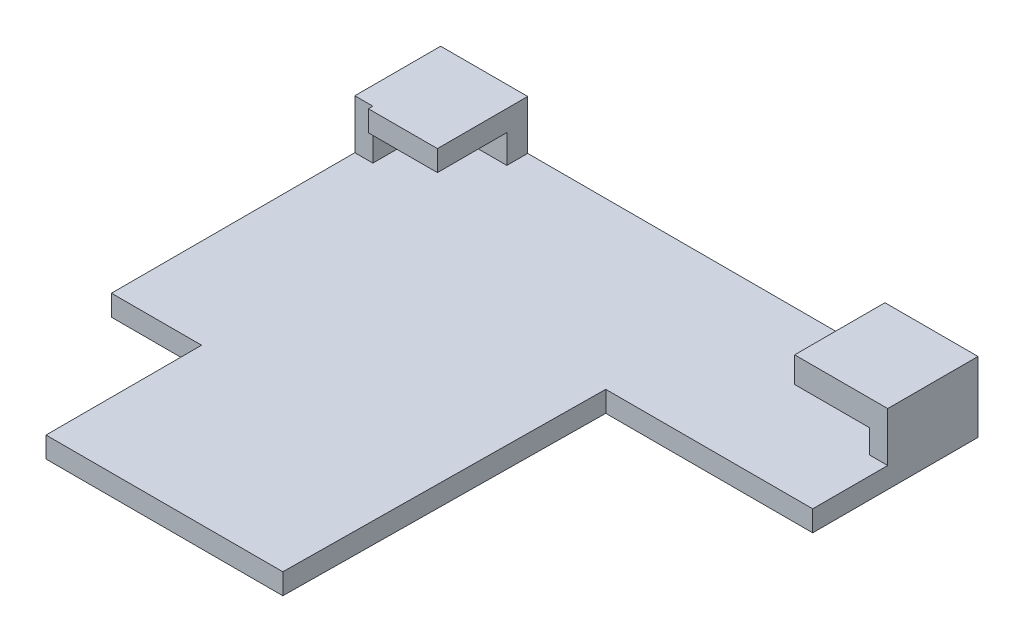
SolidWorks part; units mm, degrees
ref_plane "Front Plane" through (0, 0, 0) normal (0, 0, 1) x (1, 0, 0)
ref_plane "Top Plane" through (0, 0, 0) normal (0, 1, 0) x (1, 0, 0)
ref_plane "Right Plane" through (0, 0, 0) normal (1, 0, 0) x (0, 0, -1)
sketch "Sketch1" plane through (0, 0, 0) normal (0, 1, 0) x (1, 0, 0)
  line L0 (-75.3391, 34.6839) -> (-39.6391, 34.6839)
  line L2 (-75.3391, 34.6839) -> (-75.3391, 24.2839)
  line L8 (-75.3391, 24.2839) -> (-75.3391, 12.4839)
  line L9 (-75.3391, 12.4839) -> (-70.3391, 12.4839)
  line L10 (-70.3391, 12.4839) -> (-70.3391, 1.2839)
  line L11 (-39.6391, 34.6839) -> (-39.6391, 24.2839)
  line L12 (-39.6391, 24.2839) -> (-53.0391, 24.2839)
  line L13 (-53.0391, 24.2839) -> (-53.2891, 1.2839)
  line L14 (-70.3391, 1.2839) -> (-53.2891, 1.2839)
extrude "Boss-Extrude1" add sketch "Sketch1" along normal blind 1.5
sketch "Sketch2" plane through (0, 0, -34.6839) normal (0, 0, -1) x (-1, 0, 0)
  line L0 (18.37, 0) -> (-18.37, 0) construction
  line L1 (39.6391, 1.5) -> (75.3259, 1.5)
  line L2 (39.6391, 1.5) -> (39.6391, 0)
  line L3 (39.6391, 0) -> (75.3259, 0)
  line L4 (75.3259, 1.5) -> (75.3259, 0)
extrude "Boss-Extrude2" add sketch "Sketch2" along normal blind 1.5
sketch "Sketch3" plane through (-39.6391, 0, 0) normal (1, 0, 0) x (0, 0, -1)
  line L0 (19.195, 0) -> (-19.195, 0) construction
  line L1 (24.2839, 1.5) -> (36.1839, 1.5)
  line L2 (24.2839, 1.5) -> (24.2839, 0)
  line L3 (24.2839, 0) -> (36.1839, 0)
  line L4 (36.1839, 1.5) -> (36.1839, 0)
  line L5 (36.1839, 1.5) -> (36.1839, 0) construction
extrude "Boss-Extrude3" add sketch "Sketch3" along normal blind 1.5
sketch "Sketch4" plane through (-75.3259, 0, 0) normal (-1, 0, 0) x (0, 0, 1)
  line L0 (19.195, 0) -> (-19.195, 0) construction
  line L1 (-36.1839, 1.5) -> (-12.4839, 1.5)
  line L2 (-36.1839, 1.5) -> (-36.1839, 0)
  line L3 (-36.1839, 0) -> (-12.4839, 0)
  line L4 (-12.4839, 1.5) -> (-12.4839, 0)
  dimension "D1" = 23.7
extrude "Boss-Extrude4" add sketch "Sketch4" along normal blind 1.5
sketch "Sketch5" plane through (0, 1.5, 0) normal (0, 1, 0) x (1, 0, 0)
  line L0 (-76.8259, 12.4839) -> (-75.5259, 12.4839) construction
  line L1 (-76.8259, 12.4839) -> (-70.3391, 12.4839) construction
  line L2 (-75.5259, 36.1839) -> (-75.5259, 34.6839) construction
  line L3 (-76.8259, 36.1839) -> (-38.1391, 36.1839) construction
  line L4 (-38.1391, 34.6839) -> (-39.4391, 34.6839) construction
  line L5 (-38.1391, 36.1839) -> (-38.1391, 24.2839) construction
  line L6 (-39.4391, 24.2839) -> (-39.4391, 25.7839) construction
  line L7 (-53.0391, 24.2839) -> (-38.1391, 24.2839) construction
  line L8 (-76.8259, 35.0042) -> (-76.8259, 30.0042) construction
  line L9 (-76.8259, 12.4839) -> (-76.8259, 36.1839) construction
  line L10 (-75.5259, 34.6839) -> (-75.5259, 30.0042)
  line L11 (-75.5259, 30.0042) -> (-76.8259, 30.0042)
  line L12 (-76.8259, 30.0042) -> (-76.8259, 36.1839)
  line L13 (-76.8259, 36.1839) -> (-70.5592, 36.1839)
  line L14 (-70.5592, 36.1839) -> (-70.5592, 34.6839)
  line L15 (-70.5592, 34.6839) -> (-75.5259, 34.6839)
  line L16 (-39.4391, 34.6839) -> (-39.4391, 29.6839)
  line L17 (-39.4391, 29.6839) -> (-38.1391, 29.6839)
  line L18 (-38.1391, 29.6839) -> (-38.1391, 36.1839)
  line L19 (-38.1391, 36.1839) -> (-44.8391, 36.1839)
  line L20 (-44.8391, 36.1839) -> (-44.8391, 34.6839)
  line L21 (-44.8391, 34.6839) -> (-39.4391, 34.6839)
  dimension "D1" = 1.3
  dimension "D2" = 1.3
extrude "Boss-Extrude5" add sketch "Sketch5" along normal blind 3.55
sketch "Sketch6" plane through (0, 0, -34.6839) normal (0, 0, 1) x (1, 0, 0)
  line L0 (-70.5592, 5.05) -> (-70.5592, 1.5) construction
  line L1 (-75.5259, 5.05) -> (-70.5592, 5.05)
  line L2 (-75.5259, 5.05) -> (-75.5259, 3.55)
  line L3 (-75.5259, 3.55) -> (-70.5592, 3.55)
  line L4 (-70.5592, 5.05) -> (-70.5592, 3.55)
  line L5 (-39.4391, 5.05) -> (-39.4391, 1.5) construction
  line L6 (-44.8391, 5.05) -> (-39.4391, 5.05)
  line L7 (-44.8391, 5.05) -> (-44.8391, 3.2)
  line L8 (-44.8391, 3.2) -> (-39.4391, 3.2)
  line L9 (-39.4391, 5.05) -> (-39.4391, 3.2)
  dimension "D1" = 1.5
extrude "Boss-Extrude6" add sketch "Sketch6" along normal blind 5
